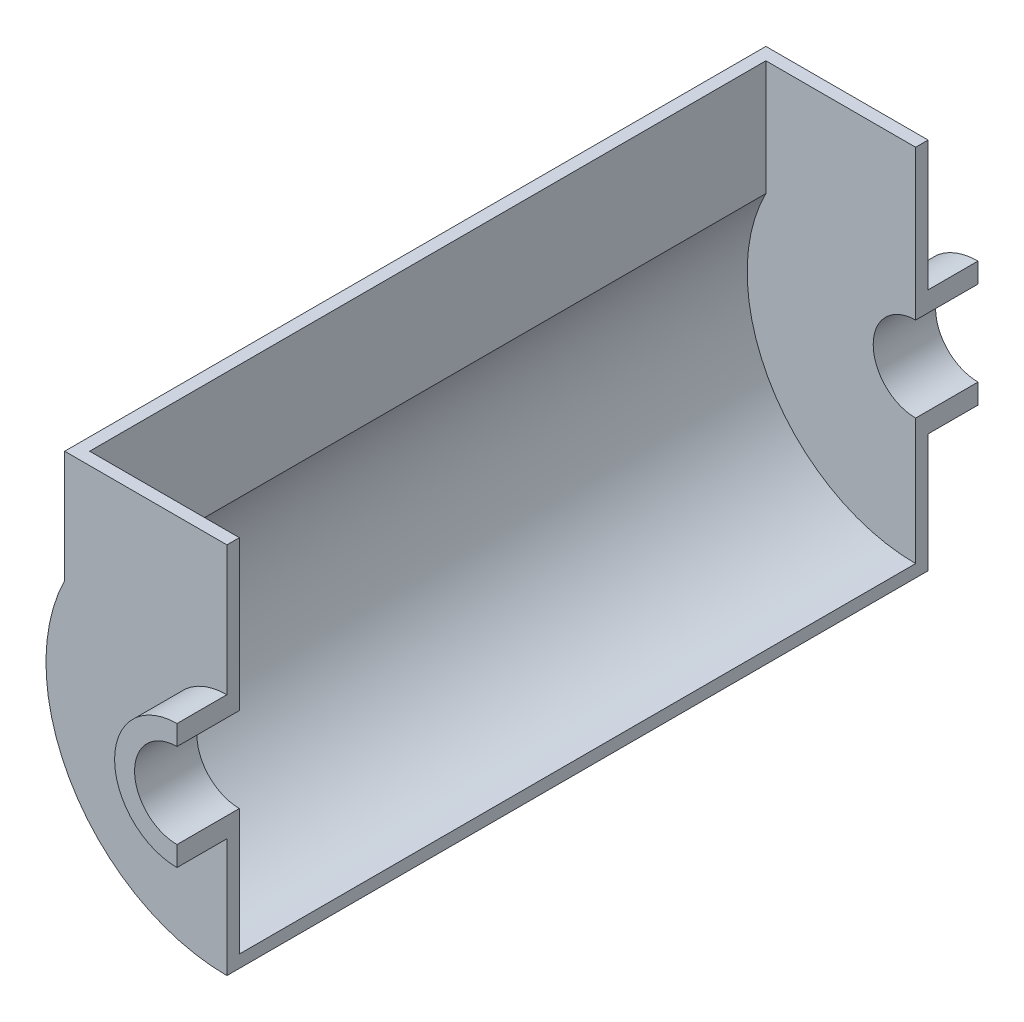
SolidWorks part; units mm, degrees
ref_plane "Front Plane" through (0, 0, 0) normal (0, 0, 1) x (1, 0, 0)
ref_plane "Top Plane" through (0, 0, 0) normal (0, 1, 0) x (1, 0, 0)
ref_plane "Right Plane" through (0, 0, 0) normal (1, 0, 0) x (0, 0, -1)
sketch "Sketch1" plane through (0, 0, 0) normal (0, 0, 1) x (1, 0, 0)
  line L0 (0, 25) -> (0, 17)
  line L1 (0, -17) -> (0, -25)
  arc A0 (0, 25) -> (0, -25) centre (0, 0) ccw
  arc A1 (0, 17) -> (0, -17) centre (0, 0) ccw
  dimension "D1" = 50
  dimension "D2" = 34
extrude "Boss-Extrude1" add sketch "Sketch1" along normal blind 20 and the other way blind 5
sketch "Sketch2" plane through (0, 0, 0) normal (0, 0, 1) x (1, 0, 0)
  line L0 (0, 25) -> (0, 77)
  line L1 (0, 77) -> (-65, 77)
  line L2 (-65, 77) -> (-65, 32.1131)
  line L3 (0, -25) -> (0, -72.5)
  arc A0 (0, 25) -> (0, -25) centre (0, 0) ccw construction
  arc A1 (0, 25) -> (0, -25) centre (0, 0) ccw
  arc A2 (-65, 32.1131) -> (0, -72.5) centre (0, 0) ccw
  point P9 (0, 0)
  dimension "D3" = 72.5
  dimension "D1" = 52
  dimension "D2" = 65
extrude "Boss-Extrude2" add sketch "Sketch2" against normal blind 5
ref_plane "Plane1" through (0, 0, -140.5) normal (0, 0, 1) x (1, 0, 0)
mirror "Mirror2" about plane through (0, 0, -140.5) normal (0, 0, 1) of bodies 102
sketch "Sketch4" plane through (0, 0, -5) normal (0, 0, -1) x (-1, 0, 0)
  line L0 (65, 77) -> (65, 32.1131) construction
  line L1 (65, 77) -> (65, 32.1131)
  line L2 (60, 77) -> (60, 30.9233)
  line L3 (65, 77) -> (60, 77)
  line L4 (0, -17) -> (0, -72.5)
  line L5 (65, 32.1131) -> (65, 77)
  line L6 (65, 77) -> (0, 77)
  line L7 (0, 77) -> (0, 17)
  line L8 (0, -17) -> (0, -72.5)
  line L9 (65, 32.1131) -> (65, 77)
  line L10 (65, 77) -> (0, 77)
  line L11 (0, 77) -> (0, 17)
  line L12 (0, -72.5) -> (0, -67.5)
  arc A0 (0, -72.5) -> (65, 32.1131) centre (0, 0) ccw construction
  arc A1 (0, -72.5) -> (65, 32.1131) centre (0, 0) ccw
  arc A2 (0, -17) -> (0, 17) centre (0, 0) ccw
  arc A3 (0, -72.5) -> (65, 32.1131) centre (0, 0) ccw
  arc A4 (0, -17) -> (0, 17) centre (0, 0) ccw
  arc A5 (0, -72.5) -> (65, 32.1131) centre (0, 0) ccw
  arc A6 (0, -67.5) -> (60, 30.9233) centre (0, 0) ccw
  dimension "D1" = 0
  dimension "D2" = 5
extrude "Boss-Extrude3" add sketch "Sketch4" along normal up to surface (271 mm away) contours L1 A1 L12 A6 L2 L3
